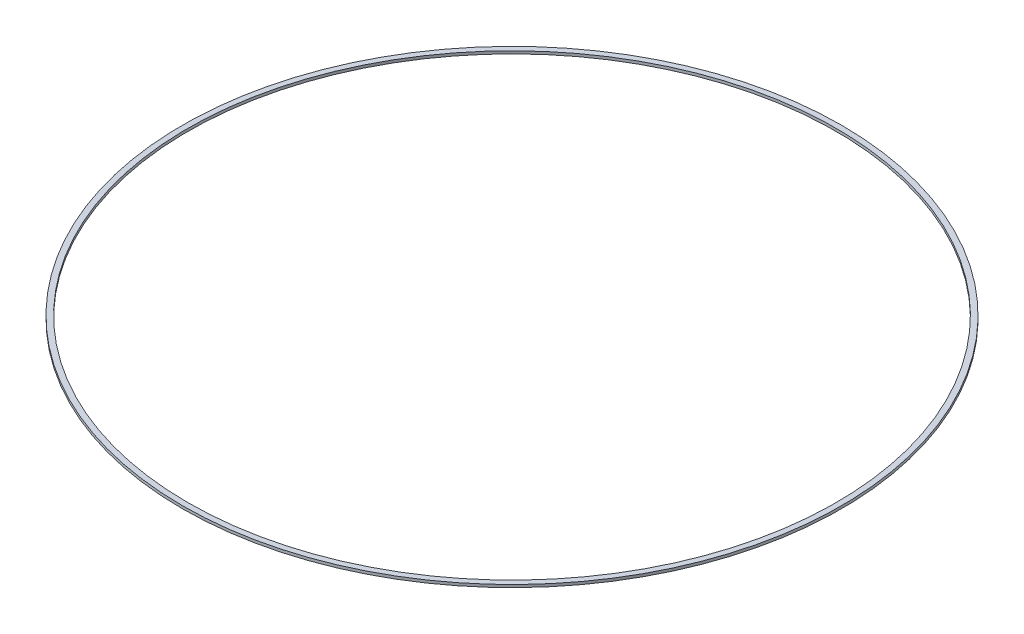
SolidWorks part; units mm, degrees
ref_plane "Front Plane" through (0, 0, 0) normal (0, 0, 1) x (1, 0, 0)
ref_plane "Top Plane" through (0, 0, 0) normal (0, 1, 0) x (1, 0, 0)
ref_plane "Right Plane" through (0, 0, 0) normal (1, 0, 0) x (0, 0, -1)
sketch "Sketch1" plane through (0, 0, 0) normal (0, 1, 0) x (1, 0, 0)
  circle A0 centre (-43.5684, -20.907) radius 154.94
  circle A1 centre (-43.5684, -20.907) radius 152.4
  dimension "D2" = 304.8
  dimension "D1" = 2.54
extrude "Boss-Extrude1" add sketch "Sketch1" along normal blind 1.27
